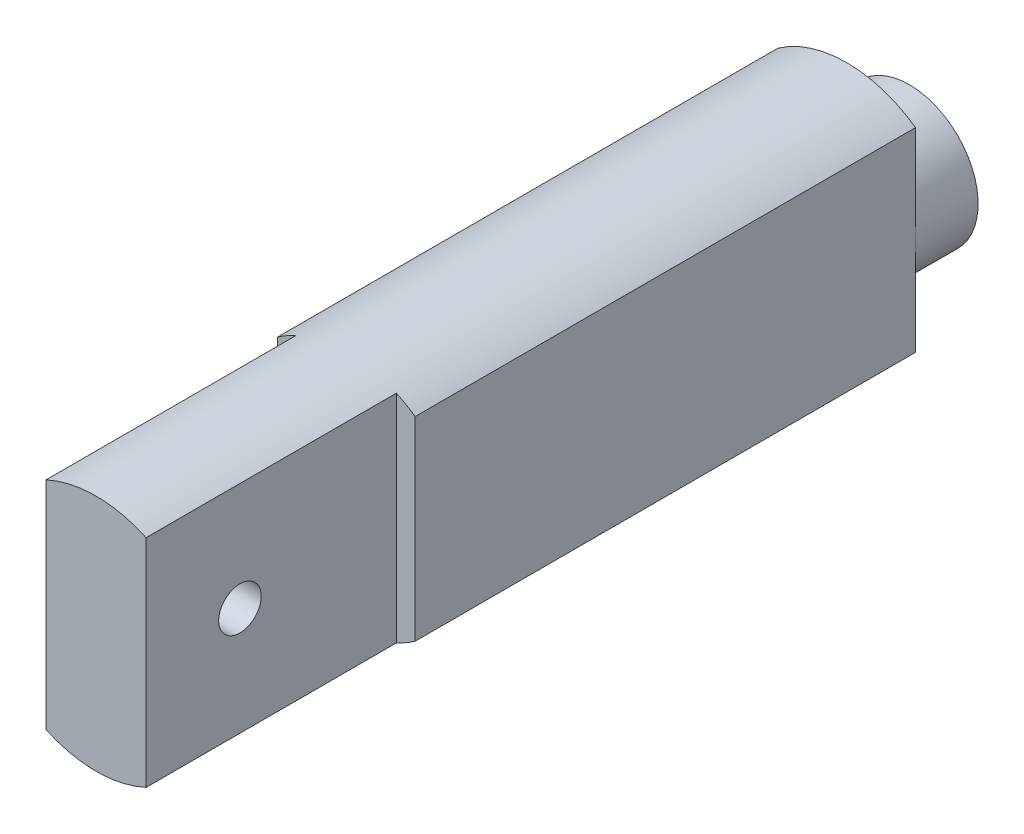
SolidWorks part; units mm, degrees
ref_plane "Front Plane" through (0, 0, 0) normal (0, 0, 1) x (1, 0, 0)
ref_plane "Top Plane" through (0, 0, 0) normal (0, 1, 0) x (1, 0, 0)
ref_plane "Right Plane" through (0, 0, 0) normal (1, 0, 0) x (0, 0, -1)
sketch "Sketch1" plane through (0, 0, 0) normal (0, 0, 1) x (1, 0, 0)
  circle A0 centre (0, 0) radius 19.05
  dimension "D1" = 38.1
extrude "Boss-Extrude1" add sketch "Sketch1" along normal blind 120
sketch "Sketch4" plane through (0, 0, 0) normal (0, 0, -1) x (-1, 0, 0)
  circle A0 centre (0, 0) radius 11
  dimension "D1" = 22
extrude "Boss-Extrude2" add sketch "Sketch4" along normal blind 10
sketch "Sketch8" plane through (0, 0, 0) normal (0, 0, -1) x (-1, 0, 0)
  line L1 (-11, 19.05) -> (11, 19.05)
  line L2 (-11, 19.05) -> (-11, -19.05)
  line L3 (-11, -19.05) -> (11, -19.05)
  line L4 (11, 19.05) -> (11, -19.05)
  circle A1 centre (0, 0) radius 19.05 construction
  circle A2 centre (0, 0) radius 11 construction
  point P6 (0, 19.05)
  point P8 (11, 0)
extrude "Cut-Extrude2" cut sketch "Sketch8" against normal through all flip side to cut
sketch "Sketch2" plane through (0, 0, 120) normal (0, 0, 1) x (1, 0, 0)
  line L0 (11, 15.5532) -> (11, -15.5532) construction
  line L1 (-8, 19.05) -> (8, 19.05)
  line L2 (-8, 19.05) -> (-8, -19.05)
  line L3 (-8, -19.05) -> (8, -19.05)
  line L4 (8, 19.05) -> (8, -19.05)
  circle A0 centre (0, 0) radius 19.05 construction
  point P4 (0, -19.05)
  point P5 (8, 0)
  dimension "D1" = 3
extrude "Cut-Extrude1" cut sketch "Sketch2" against normal blind 40 flip side to cut
hole_wizard "M8x1.25 Tapped Hole1" positions "Sketch6" profile "Sketch7" tap size "M8x1.25" standard "ANSI Metric" end condition through all
sketch "Sketch6" plane through (8, 0, 0) normal (1, 0, 0) x (0, 0, -1)
  line L2 (-120, -17.2888) -> (-120, 17.2888) construction
  point P0 (-105, 0)
  point P18 (0, 0)
  dimension "D1" = 15
sketch "Sketch7" plane through (8, 0, 105) normal (0, 1, 0) x (0, 0, -1)
  line L0 (0, 0) -> (0, 19)
  line L1 (0, 19) -> (3.4, 19)
  line L2 (3.4, 19) -> (3.4, 0)
  line L5 (3.4, 0) -> (0, 0)
  line L11 (0, -6.35) -> (0, 107.95) construction
  dimension "Thru Tap Drill Dia." = 6.8
  dimension "Thru Tap Drill Depth" = 19
cosmetic thread "Hole Thread1" parameters "D2"=8
